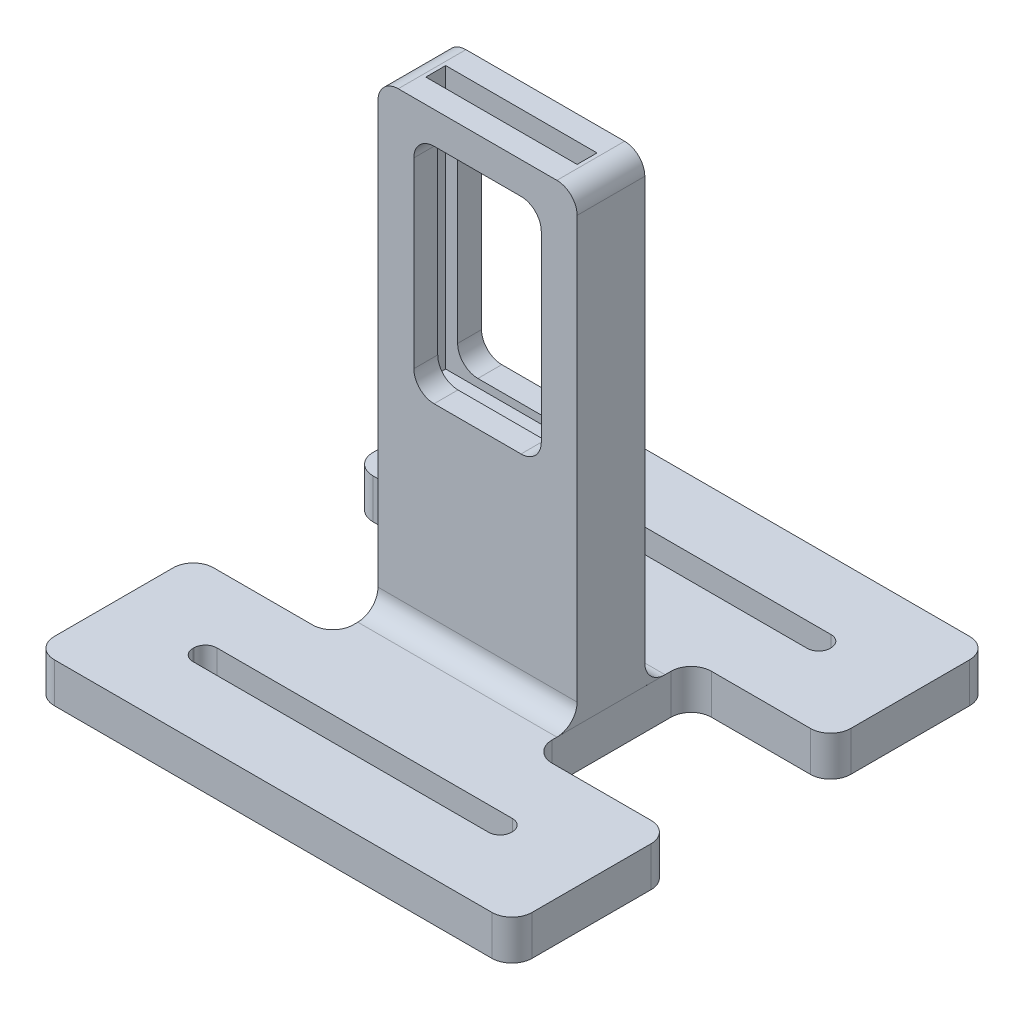
SolidWorks part; units mm, degrees
ref_plane "Front Plane" through (0, 0, 0) normal (0, 0, 1) x (1, 0, 0)
ref_plane "Top Plane" through (0, 0, 0) normal (0, 1, 0) x (1, 0, 0)
ref_plane "Right Plane" through (0, 0, 0) normal (1, 0, 0) x (0, 0, -1)
sketch "Sketch1" plane through (0, 0, 0) normal (0, 1, 0) x (1, 0, 0)
  line L1 (-29.9996, -29.9264) -> (30.0004, -29.9264)
  line L2 (-29.9996, -29.9264) -> (-29.9996, -9.9264)
  line L3 (-29.9996, 30.0736) -> (30.0004, 30.0736)
  line L4 (30.0004, -29.9264) -> (30.0004, -9.9264)
  line L5 (0.0004, -9.9264) -> (0.0004, 10.0736) construction
  line L6 (30.0004, -9.9264) -> (12.5004, -9.9264)
  line L7 (12.5004, 10.0736) -> (-12.4996, 10.0736) construction
  line L8 (12.5004, 10.0736) -> (12.5004, -9.9264)
  line L9 (12.5004, -9.9264) -> (-12.4996, -9.9264) construction
  line L11 (-29.9996, 30.0736) -> (-29.9996, 10.0736)
  line L12 (30.0004, 30.0736) -> (30.0004, 10.0736)
  line L13 (-12.4996, 10.0736) -> (-12.4996, -9.9264)
  line L14 (12.5004, 10.0736) -> (-12.4996, -9.9264) construction
  line L15 (12.5004, -9.9264) -> (-12.4996, 10.0736) construction
  line L16 (-12.4996, -9.9264) -> (-29.9996, -9.9264)
  line L17 (30.0004, 10.0736) -> (12.5004, 10.0736)
  line L18 (-12.4996, 10.0736) -> (-29.9996, 10.0736)
  point P0 (0, 0)
  point P11 (0.0004, 0.0736)
  dimension "D1" = 60
  dimension "D2" = 60
  dimension "D3" = 25
  dimension "D5" = 20
  dimension "D6" = 20
extrude "Boss-Extrude1" add sketch "Sketch1" along normal blind 5
sketch "Sketch2" plane through (0, 5, 0) normal (0, 1, 0) x (1, 0, 0)
  line L0 (-29.9996, 20.0736) -> (30.0004, 20.0736) construction
  line L1 (-29.9996, 30.0736) -> (-29.9996, 10.0736) construction
  line L2 (30.0004, 30.0736) -> (30.0004, 10.0736) construction
  line L8 (-29.9996, -19.9264) -> (30.0004, -19.9264) construction
  line L9 (-29.9996, -29.9264) -> (-29.9996, -9.9264) construction
  line L10 (30.0004, -29.9264) -> (30.0004, -9.9264) construction
  line L17 (-18.5492, 18.5736) -> (18.55, 18.5736)
  line L18 (-19.9992, 20.0236) -> (-19.9992, 20.1236)
  line L19 (-18.5492, 21.5736) -> (18.55, 21.5736)
  line L20 (20, 20.0236) -> (20, 20.1236)
  line L21 (-19.9992, 18.5736) -> (20, 21.5736) construction
  line L22 (-19.9992, 21.5736) -> (20, 18.5736) construction
  line L23 (-18.5496, -21.4264) -> (18.5504, -21.4264)
  line L24 (-19.9996, -19.9764) -> (-19.9996, -19.8764)
  line L25 (-18.5496, -18.4264) -> (18.5504, -18.4264)
  line L26 (20.0004, -19.9764) -> (20.0004, -19.8764)
  line L27 (-19.9996, -21.4264) -> (20.0004, -18.4264) construction
  line L28 (-19.9996, -18.4264) -> (20.0004, -21.4264) construction
  arc A0 (-18.5496, -21.4264) -> (-19.9996, -19.9764) centre (-18.5496, -19.9764) cw
  arc A1 (-19.9996, -19.8764) -> (-18.5496, -18.4264) centre (-18.5496, -19.8764) cw
  arc A2 (18.5504, -21.4264) -> (20.0004, -19.9764) centre (18.5504, -19.9764) ccw
  arc A3 (18.5504, -18.4264) -> (20.0004, -19.8764) centre (18.5504, -19.8764) cw
  arc A4 (18.55, 18.5736) -> (20, 20.0236) centre (18.55, 20.0236) ccw
  arc A5 (-18.5492, 18.5736) -> (-19.9992, 20.0236) centre (-18.5492, 20.0236) cw
  arc A6 (18.55, 21.5736) -> (20, 20.1236) centre (18.55, 20.1236) cw
  arc A7 (-19.9992, 20.1236) -> (-18.5492, 21.5736) centre (-18.5492, 20.1236) cw
  point P32 (0.0004, 20.0736)
  point P37 (0.0004, -19.9264)
  dimension "D3" = 1.45
  dimension "D1" = 3
  dimension "D2" = 3
  dimension "D4" = 10
extrude "Cut-Extrude1" cut sketch "Sketch2" against normal through all
fillet "Fillet1" radius 2.54 12 edges at (-29.9996, 2.5, -30.0736) (-29.9996, 2.5, 29.9264) (30.0004, 2.5, 29.9264) (30.0004, 2.5, -30.0736) (30.0004, 2.5, -10.0736) (30.0004, 2.5, 9.9264) (12.5004, 2.5, 9.9264) (12.5004, 2.5, -10.0736) (-29.9996, 2.5, -10.0736) (-12.4996, 2.5, -10.0736) (-12.4996, 2.5, 9.9264) (-29.9996, 2.5, 9.9264)
sketch "Sketch3" plane through (0, 5, 0) normal (0, 1, 0) x (1, 0, 0)
  line L1 (-12.5, 4.25) -> (12.5, 4.25)
  line L2 (-12.5, 4.25) -> (-12.5, -4.25)
  line L3 (-12.5, -4.25) -> (12.5, -4.25)
  line L4 (12.5, 4.25) -> (12.5, -4.25)
  line L5 (-12.5, 4.25) -> (12.5, -4.25) construction
  line L6 (-12.5, -4.25) -> (12.5, 4.25) construction
  point P0 (0, 0)
  dimension "D1" = 8.5
  dimension "D2" = 25
extrude "Boss-Extrude2" add sketch "Sketch3" along normal blind 25
sketch "Sketch4" plane through (0, 30, 0) normal (0, 1, 0) x (1, 0, 0)
  line L0 (-12.5, 4.25) -> (-12.5, -4.25) construction
  line L1 (12.5, 1.25) -> (-12.5, 1.25)
  line L2 (12.5, 1.25) -> (12.5, -1.25)
  line L3 (12.5, -1.25) -> (-12.5, -1.25)
  line L4 (-12.5, 1.25) -> (-12.5, -1.25)
  line L5 (12.5, 1.25) -> (-12.5, -1.25) construction
  line L6 (12.5, -1.25) -> (-12.5, 1.25) construction
  line L8 (9.5, 1.25) -> (-9.5, 1.25)
  line L9 (9.5, 1.25) -> (9.5, -1.25)
  line L10 (9.5, -1.25) -> (-9.5, -1.25)
  line L11 (-9.5, 1.25) -> (-9.5, -1.25)
  line L12 (9.5, 1.25) -> (-9.5, -1.25) construction
  line L13 (9.5, -1.25) -> (-9.5, 1.25) construction
  point P0 (0, 0)
  point P8 (0, 0)
  line M4 (12.5, -4.25) -> (12.5, 4.25)
  line M5 (12.5, 4.25) -> (-12.5, 4.25)
  line M6 (-12.5, 4.25) -> (-12.5, -4.25)
  line M7 (-12.5, -4.25) -> (12.5, -4.25)
  dimension "D1" = 2.5
  dimension "D2" = 19
extrude "Boss-Extrude3" add sketch "Sketch4" along normal blind 33 contours L3 M4 M6 M7 | L1 L9 L3 M4 | L1 M4 M5 M6 | L11 L1 L3 M6
sketch "Sketch5" plane through (0, 0, -4.25) normal (0, 0, -1) x (-1, 0, 0)
  line L0 (-12.5, 30) -> (12.5, 30) construction
  line L1 (-12.5, 63) -> (-12.5, 5) construction
  line L2 (12.5, 63) -> (12.5, 5) construction
  line L3 (-12.5, 63) -> (12.5, 63) construction
  line L4 (-12.5, 60) -> (12.5, 60) construction
  line L5 (0, 60) -> (0, 30) construction
  line L7 (-5.46, 31) -> (5.46, 31)
  line L8 (-8, 33.54) -> (-8, 56.46)
  line L9 (-5.46, 59) -> (5.46, 59)
  line L10 (8, 33.54) -> (8, 56.46)
  line L11 (-8, 31) -> (8, 59) construction
  line L12 (-8, 59) -> (8, 31) construction
  arc A0 (-5.46, 31) -> (-8, 33.54) centre (-5.46, 33.54) cw
  arc A1 (5.46, 31) -> (8, 33.54) centre (5.46, 33.54) ccw
  arc A2 (5.46, 59) -> (8, 56.46) centre (5.46, 56.46) cw
  arc A3 (-8, 56.46) -> (-5.46, 59) centre (-5.46, 56.46) cw
  point P12 (0, 45)
  dimension "D5" = 2.54
  dimension "D1" = 33
  dimension "D2" = 30
  dimension "D3" = 28
  dimension "D4" = 16
extrude "Cut-Extrude2" cut sketch "Sketch5" against normal through all
fillet "Fillet2" radius 2.54 4 edges at (0.0002, 5, 4.25) (0.0002, 5, -4.25) (12.5, 63, 0) (-12.5, 63, 0)
